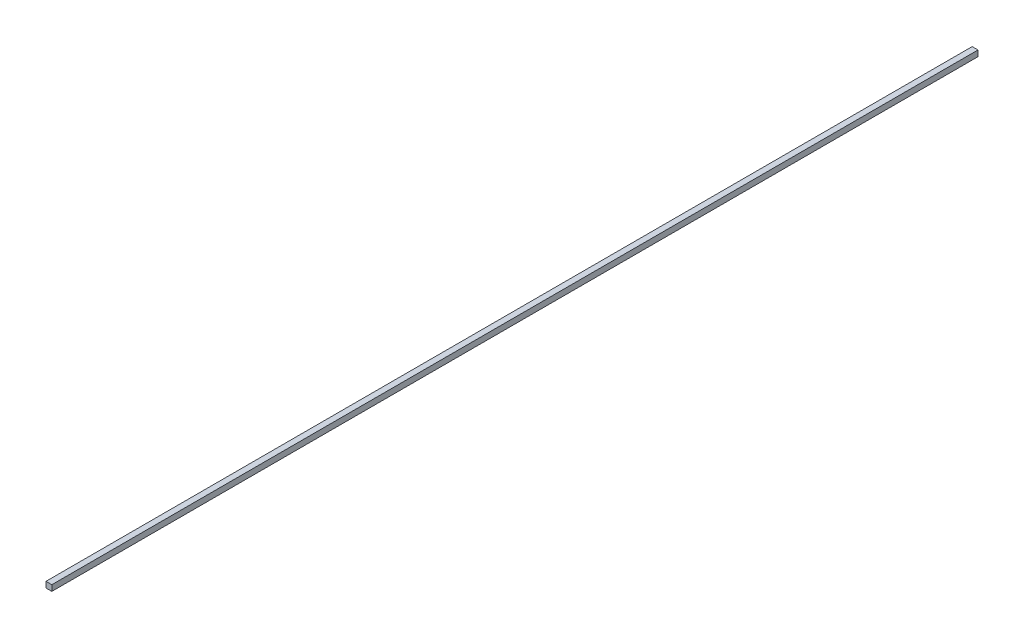
SolidWorks part; units mm, degrees
ref_plane "Front Plane" through (0, 0, 0) normal (0, 0, 1) x (1, 0, 0)
ref_plane "Top Plane" through (0, 0, 0) normal (0, 1, 0) x (1, 0, 0)
ref_plane "Right Plane" through (0, 0, 0) normal (1, 0, 0) x (0, 0, -1)
sketch "Sketch1" plane through (0, 0, 0) normal (0, 0, 1) x (1, 0, 0)
  line L1 (1, 1) -> (-1, 1)
  line L2 (1, 1) -> (1, -1)
  line L3 (1, -1) -> (-1, -1)
  line L4 (-1, 1) -> (-1, -1)
  line L5 (1, 1) -> (-1, -1) construction
  line L6 (1, -1) -> (-1, 1) construction
  point P0 (0, 0)
  dimension "D1" = 2
  dimension "D2" = 2
extrude "Boss-Extrude1" add sketch "Sketch1" along normal up to surface (317.4188 mm away)
equation "\"D2@Sketch1\"=\"D1@Sketch1\""
